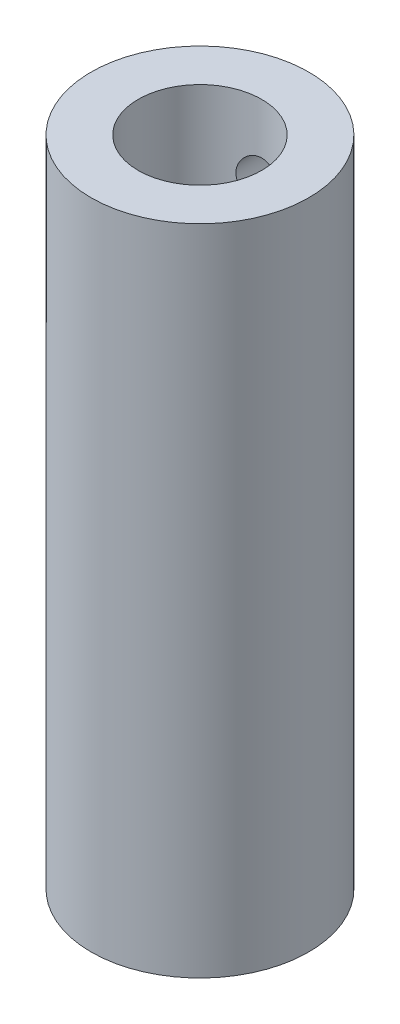
SolidWorks part; units mm, degrees
ref_plane "Ön Düzlem" through (0, 0, 0) normal (0, 0, 1) x (1, 0, 0)
ref_plane "Üst Düzlem" through (0, 0, 0) normal (0, 1, 0) x (1, 0, 0)
ref_plane "Sağ Düzlem" through (0, 0, 0) normal (1, 0, 0) x (0, 0, -1)
sketch "Çizim1" plane through (0, 0, 0) normal (0, 1, 0) x (1, 0, 0)
  circle A0 centre (0, 0) radius 2.75
  circle A1 centre (0, 0) radius 7.5
  dimension "D1" = 5.5
  dimension "D2" = 15
extrude "Yükseklik-Ekstrüzyon1" add sketch "Çizim1" along normal blind 15
sketch "Çizim2" plane through (0, 15, 0) normal (0, 1, 0) x (1, 0, 0)
  circle A0 centre (0, 0) radius 4.25
  circle A1 centre (0, 0) radius 7.5
  circle A2 centre (0, 0) radius 7.5 construction
  dimension "D1" = 8.5
extrude "Yükseklik-Ekstrüzyon2" add sketch "Çizim2" along normal blind 30
sketch "Çizim3" plane through (0, 0, 0) normal (0, 0, 1) x (1, 0, 0)
  line L0 (7.5, 45) -> (-7.5, 45) construction
  circle A0 centre (0, 40) radius 1.5
  circle A1 centre (0, 35) radius 1.5
  circle A2 centre (0, 30) radius 1.5
  circle A3 centre (0, 9) radius 1.5
  circle A4 centre (0, 4) radius 1.5
  dimension "D1" = 3
  dimension "D2" = 4
  dimension "D3" = 5
  dimension "D4" = 5
  dimension "D5" = 5
  dimension "D6" = 5
extrude "Kes-Ekstrüzyon1" cut sketch "Çizim3" against normal blind 30
